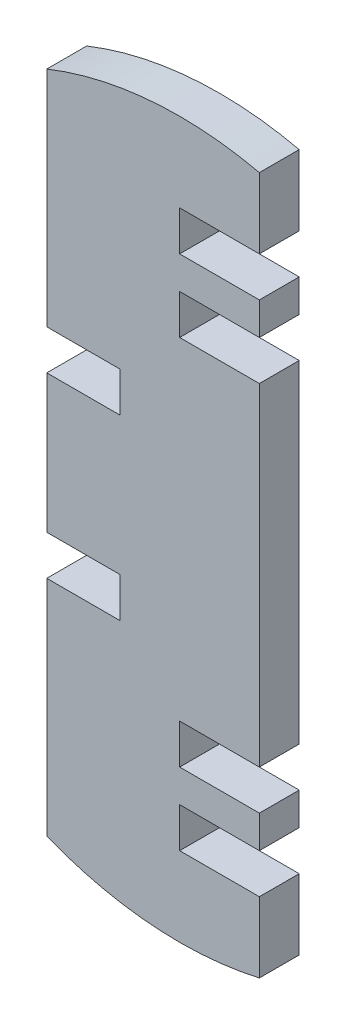
SolidWorks part; units mm, degrees
ref_plane "Front" through (0, 0, 0) normal (0, 0, 1) x (1, 0, 0)
ref_plane "Top" through (0, 0, 0) normal (0, 1, 0) x (1, 0, 0)
ref_plane "Right" through (0, 0, 0) normal (1, 0, 0) x (0, 0, -1)
sketch "Sketch1" plane through (0, 0, 0) normal (0, 0, 1) x (1, 0, 0)
  line L0 (693.9387, -90.7837) -> (693.9387, -115.7837)
  line L1 (677.9387, -78.2837) -> (677.9387, -95.0878)
  line L2 (677.9387, -98.0878) -> (677.9387, -108.4795)
  line L3 (693.9387, -87.7837) -> (693.9387, -85.3337)
  line L4 (693.9387, -124.2336) -> (693.9387, -129.5325)
  line L5 (687.9387, -118.7837) -> (687.9387, -115.7837)
  line L6 (687.9387, -115.7837) -> (693.9387, -115.7837)
  line L7 (687.9387, -118.7837) -> (693.9387, -118.7837)
  line L8 (677.9387, -108.4795) -> (683.4675, -108.4795)
  line L9 (683.4675, -108.4795) -> (683.4675, -111.4795)
  line L10 (683.4675, -111.4795) -> (677.9387, -111.4795)
  line L11 (683.4675, -95.0878) -> (677.9387, -95.0878)
  line L12 (687.9387, -121.2336) -> (693.9387, -121.2336)
  line L13 (683.4675, -98.0878) -> (683.4675, -95.0878)
  line L14 (693.9387, -118.7837) -> (693.9387, -121.2336)
  line L15 (677.9387, -103.2837) -> (693.9387, -103.2837) construction
  line L16 (677.9387, -128.2837) -> (677.9387, -111.4795)
  line L17 (677.9387, -98.0878) -> (683.4675, -98.0878)
  line L18 (687.9387, -121.2336) -> (687.9387, -124.2336)
  line L19 (687.9387, -124.2336) -> (693.9387, -124.2336)
  line L20 (687.9387, -87.7837) -> (693.9387, -87.7837)
  line L21 (687.9387, -90.7837) -> (693.9387, -90.7837)
  line L22 (687.9387, -82.3337) -> (693.9387, -82.3337)
  line L23 (687.9387, -87.7837) -> (687.9387, -90.7837)
  line L24 (687.9387, -85.3337) -> (687.9387, -82.3337)
  line L25 (687.9387, -85.3337) -> (693.9387, -85.3337)
  line L26 (693.9387, -82.3337) -> (693.9387, -77.0349)
  arc A0 (677.9387, -78.2837) -> (693.9387, -77.0349) centre (687.9387, -103.2837) cw
  arc A1 (677.9387, -128.2837) -> (693.9387, -129.5325) centre (687.9387, -103.2837) ccw
  dimension "D1" = 3
  dimension "D2" = 12.5
  dimension "D3" = 16
  dimension "D4" = 3
  dimension "D5" = 6
  dimension "D6" = 25
  dimension "D7" = 3
extrude "Base-Extrude" add sketch "Sketch1" along normal blind 3
